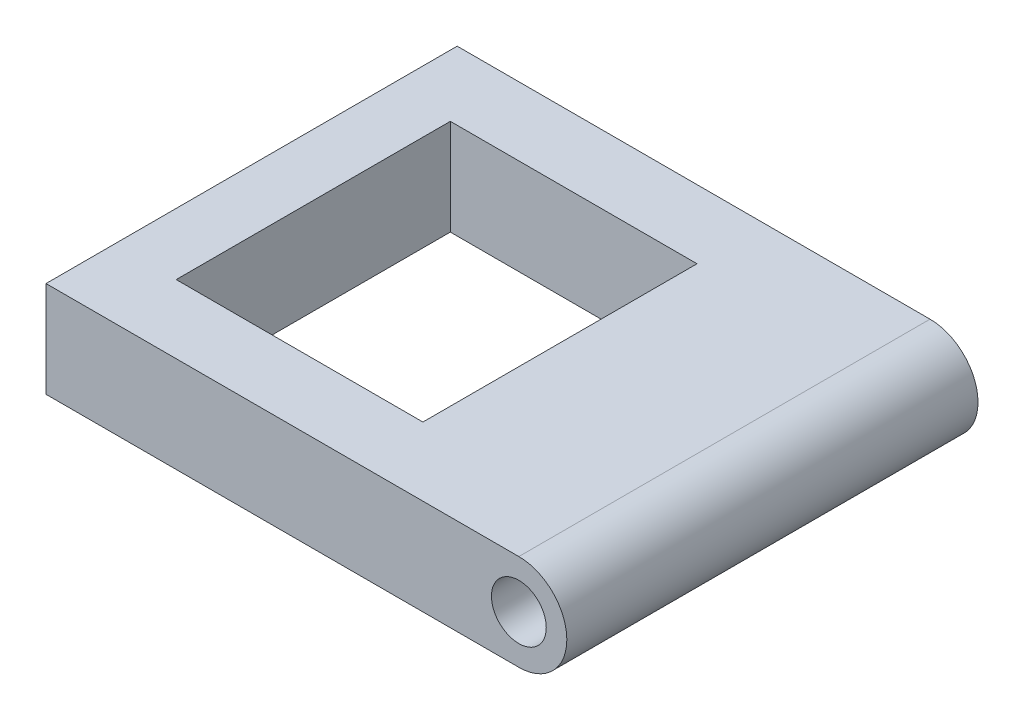
SolidWorks part; units mm, degrees
ref_plane "前视基准面" through (0, 0, 0) normal (0, 0, 1) x (1, 0, 0)
ref_plane "上视基准面" through (0, 0, 0) normal (0, 1, 0) x (1, 0, 0)
ref_plane "右视基准面" through (0, 0, 0) normal (1, 0, 0) x (0, 0, -1)
other "Configuration Table"
sketch "草图1" plane through (0, 0, 0) normal (0, 1, 0) x (1, 0, 0)
  line L0 (0, 0) -> (55, 0)
  line L2 (0, 0) -> (0, 60)
  line L3 (0, 60) -> (55, 60)
  line L4 (55, 0) -> (55, 60)
  line L6 (9, 10) -> (9, 50)
  line L7 (9, 50) -> (45, 50)
  line L8 (45, 50) -> (45, 10)
  line L9 (45, 10) -> (9, 10)
extrude "凸台-拉伸1" add sketch "草图1" along normal blind 14
sketch "草图2" plane through (0, 0, 0) normal (0, 0, 1) x (1, 0, 0)
  line L0 (55, 14) -> (69, 14)
  line L1 (55, 0) -> (69, 0)
  line L2 (55, 14) -> (55, 0)
  arc A0 (69, 0) -> (69, 14) centre (69, 7) ccw
  circle A1 centre (69, 7) radius 4
  point P8 (0, 0)
extrude "凸台-拉伸2" add sketch "草图2" against normal blind 60
